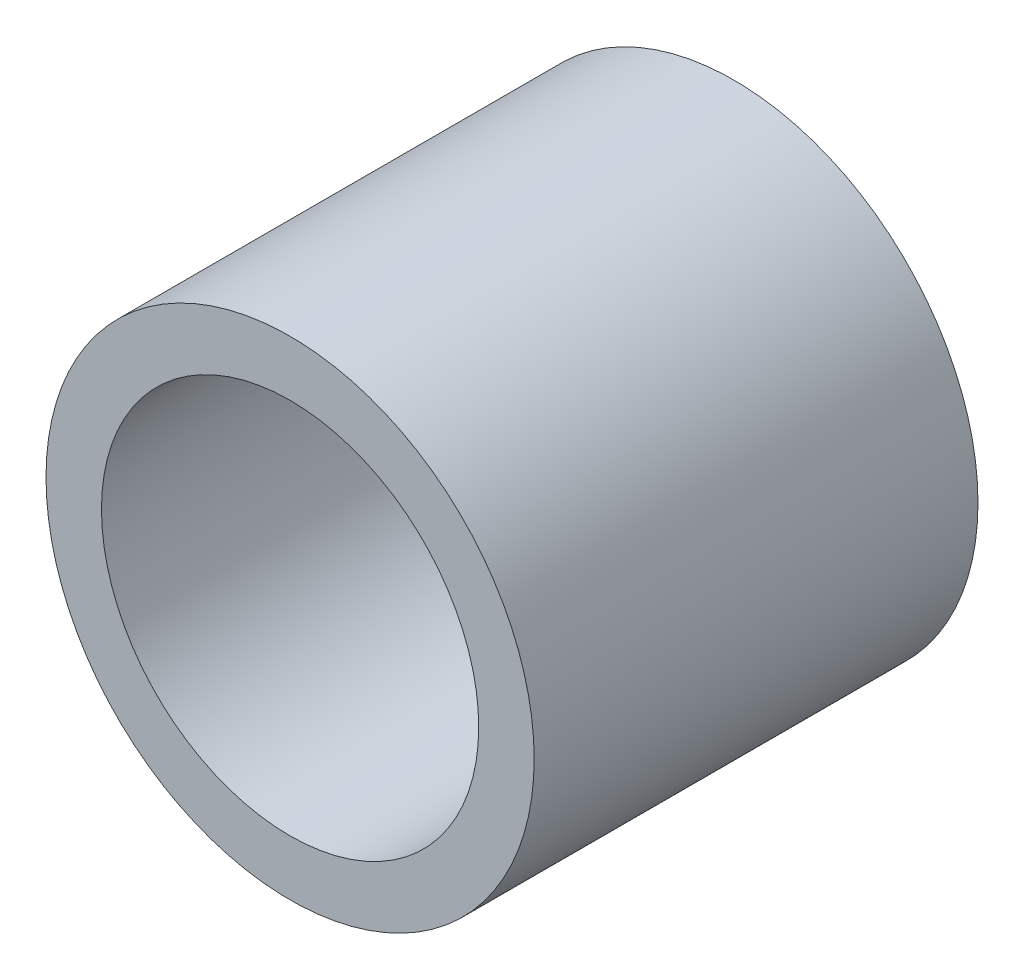
SolidWorks part; units mm, degrees
ref_plane "Front Plane" through (0, 0, 0) normal (0, 0, 1) x (1, 0, 0)
ref_plane "Top Plane" through (0, 0, 0) normal (0, 1, 0) x (1, 0, 0)
ref_plane "Right Plane" through (0, 0, 0) normal (1, 0, 0) x (0, 0, -1)
sketch "Sketch1" plane through (0, 0, 0) normal (0, 0, 1) x (1, 0, 0)
  circle A0 centre (0, 0) radius 17
  circle A1 centre (0, 0) radius 22
  dimension "D1" = 34
  dimension "D2" = 44
extrude "Boss-Extrude1" add sketch "Sketch1" along normal blind 40
